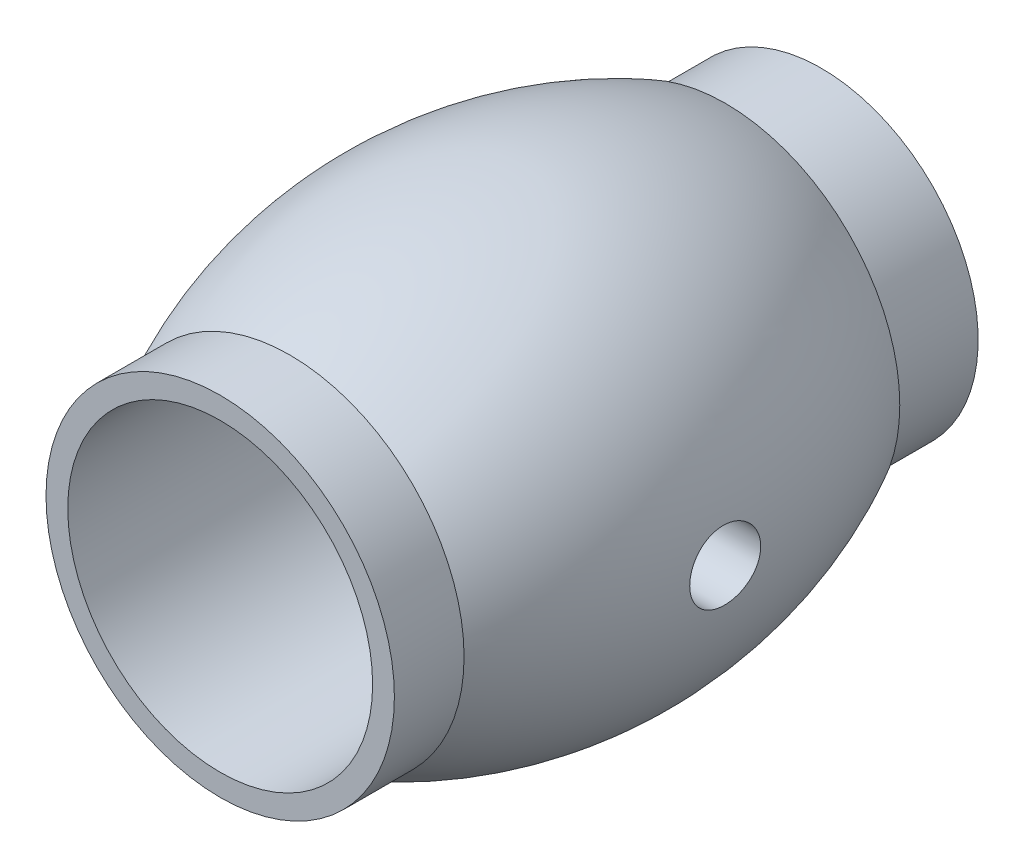
SolidWorks part; units mm, degrees
ref_plane "Front Plane" through (0, 0, 0) normal (0, 0, 1) x (1, 0, 0)
ref_plane "Top Plane" through (0, 0, 0) normal (0, 1, 0) x (1, 0, 0)
ref_plane "Right Plane" through (0, 0, 0) normal (1, 0, 0) x (0, 0, -1)
sketch "Sketch1" plane through (0, 0, 0) normal (0, 0, 1) x (1, 0, 0)
  circle A0 centre (0, 0) radius 25.4
  dimension "D1" = 50.8
extrude "Boss-Extrude1" add sketch "Sketch1" against normal blind 10.16
sketch "Sketch3" plane through (0, 0, 0) normal (1, 0, 0) x (0, 0, -1)
  line L0 (-91.4444, 0) -> (91.4444, 0) construction
  line L2 (10.16, 25.4) -> (10.16, 0)
  line L3 (10.16, -25.4) -> (10.16, 25.4) construction
  line L4 (10.16, 0) -> (73.6914, 0)
  line L5 (73.6914, 0) -> (73.6914, 25.4)
  arc A0 (10.16, 25.4) -> (73.6914, 25.4) centre (41.9257, -35.3796) cw
  point P10 (0, 0)
  dimension "D1" = 68.58
  dimension "D2" = 63.5314
revolve "Revolve1" add sketch "Sketch3" angle 360 about L0
sketch "Sketch4" plane through (0, 0, 0) normal (0, 0, 1) x (1, 0, 0)
  circle A0 centre (0, 0) radius 22.225
  dimension "D1" = 44.45
extrude "Cut-Extrude1" cut sketch "Sketch4" against normal through all
sketch "Sketch5" plane through (0, 0, -73.6914) normal (0, 0, -1) x (-1, 0, 0)
  circle A0 centre (0, 0) radius 22.86
  dimension "D1" = 45.72
extrude "Boss-Extrude2" add sketch "Sketch5" along normal blind 13.97 separate body
sketch "Sketch6" plane through (0, 0, -87.6614) normal (0, 0, -1) x (-1, 0, 0)
  circle A0 centre (0, 0) radius 22.225
  dimension "D1" = 44.45
extrude "Cut-Extrude2" cut sketch "Sketch6" against normal through all
sketch "Sketch7" plane through (0, 0, 0) normal (1, 0, 0) x (0, 0, -1)
  circle A0 centre (40.64, 0) radius 5.08
  dimension "D2" = 10.16
  dimension "D1" = 40.64
extrude "Cut-Extrude3" cut sketch "Sketch7" against normal mid plane 254
